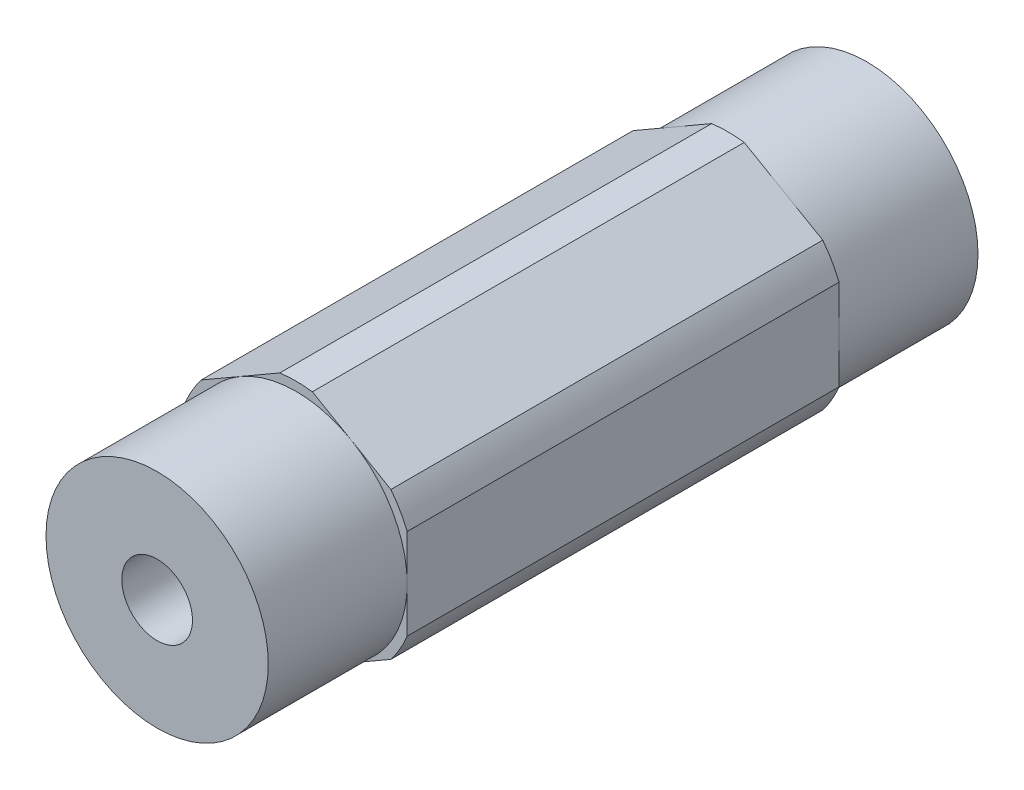
SolidWorks part; units mm, degrees
ref_plane "Front Plane" through (0, 0, 0) normal (0, 0, 1) x (1, 0, 0)
ref_plane "Top Plane" through (0, 0, 0) normal (0, 1, 0) x (1, 0, 0)
ref_plane "Right Plane" through (0, 0, 0) normal (1, 0, 0) x (0, 0, -1)
sketch "Sketch1" plane through (0, 0, 0) normal (0, 0, 1) x (1, 0, 0)
  line L1 (6.35, 3.6662) -> (0, 7.3323)
  line L2 (0, 7.3323) -> (-6.35, 3.6662)
  line L3 (-6.35, 3.6662) -> (-6.35, -3.6662)
  line L4 (-6.35, -3.6662) -> (0, -7.3323)
  line L5 (0, -7.3323) -> (6.35, -3.6662)
  line L6 (6.35, -3.6662) -> (6.35, 3.6662)
  circle A0 centre (0, 0) radius 6.35 construction
  circle A1 centre (0, 0) radius 6.858
  dimension "D1" = 12.7
  dimension "D2" = 13.716
extrude "Boss-Extrude1" add sketch "Sketch1" along normal mid plane 24.6746 contours L6 A1 L1 L2 L3 L4 L5
sketch "Sketch2" plane through (0, 0, 12.3373) normal (0, 0, 1) x (1, 0, 0)
  circle A0 centre (0, 0) radius 6.35
  dimension "D1" = 12.7
extrude "Boss-Extrude2" add sketch "Sketch2" along normal blind 7.9375
mirror "Mirror1" about plane through (0, 0, 0) normal (0, 0, 1) of "Boss-Extrude2"
hole_wizard "#10-32 Tapped Hole1" positions "3DSketch1" profile "Sketch3" tap size "#10-32" standard "ANSI Inch"
sketch3d "3DSketch1"
  line L0 (0, 0, 20.2748) -> (0, 0, 12.3373) construction
  line L1 (0, 0, -20.2748) -> (0, 0, -12.3373) construction
  point P0 (0, 0, 20.2748)
  point P4 (0, 0, -20.2748)
sketch "Sketch3" plane through (0, 0, 20.2748) normal (1, 0, 0) x (0, -1, 0)
  line L0 (0, 0) -> (0, 16.2908)
  line L1 (0, 16.2908) -> (2.0193, 15.0774)
  line L2 (2.0193, 15.0774) -> (2.0193, 0)
  line L5 (2.0193, 0) -> (0, 0)
  line L10 (0, 16.2908) -> (-2.0193, 15.0774) construction
  line L11 (0, -6.35) -> (0, 107.95) construction
  dimension "Tap Drill Dia." = 4.0386
  dimension "Tap Drill Depth" = 15.0774
  dimension "Drill Angle" = 118
cosmetic thread "Hole Thread1" parameters "D1"=12.7, "D2"=4.826
cosmetic thread "Hole Thread2" parameters "D1"=12.7, "D2"=4.826
